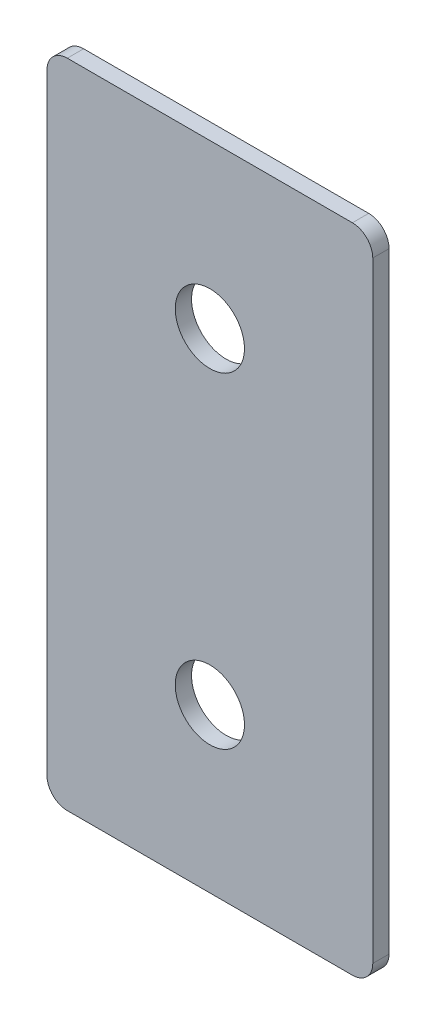
SolidWorks part; units mm, degrees
material "5052-H32"
ref_plane "Front Plane" through (0, 0, 0) normal (0, 0, 1) x (1, 0, 0)
ref_plane "Top Plane" through (0, 0, 0) normal (0, 1, 0) x (1, 0, 0)
ref_plane "Right Plane" through (0, 0, 0) normal (1, 0, 0) x (0, 0, -1)
sketch "Sketch1" plane through (0, 0, 0) normal (0, 0, 1) x (1, 0, 0)
  line L1 (20, -40) -> (-20, -40)
  line L2 (20, -40) -> (20, 40)
  line L3 (20, 40) -> (-20, 40)
  line L4 (-20, -40) -> (-20, 40)
  line L5 (20, -40) -> (-20, 40) construction
  line L6 (20, 40) -> (-20, -40) construction
  point P0 (0, 0)
  dimension "D1" = 40
  dimension "D2" = 80
extrude "Boss-Extrude1" add sketch "Sketch1" along normal blind 2
sketch "Sketch2" plane through (0, 0, 2) normal (0, 0, 1) x (1, 0, 0)
  circle A0 centre (0, 20) radius 4.25
  circle A1 centre (0, -20) radius 4.25
  dimension "D3" = 8.5
  dimension "D1" = 40
  dimension "D2" = 20
extrude "Cut-Extrude1" cut sketch "Sketch2" against normal blind 2
fillet "Fillet1" radius 2.5 4 edges at (20, -40, 1) (-20, -40, 1) (-20, 40, 1) (20, 40, 1)
